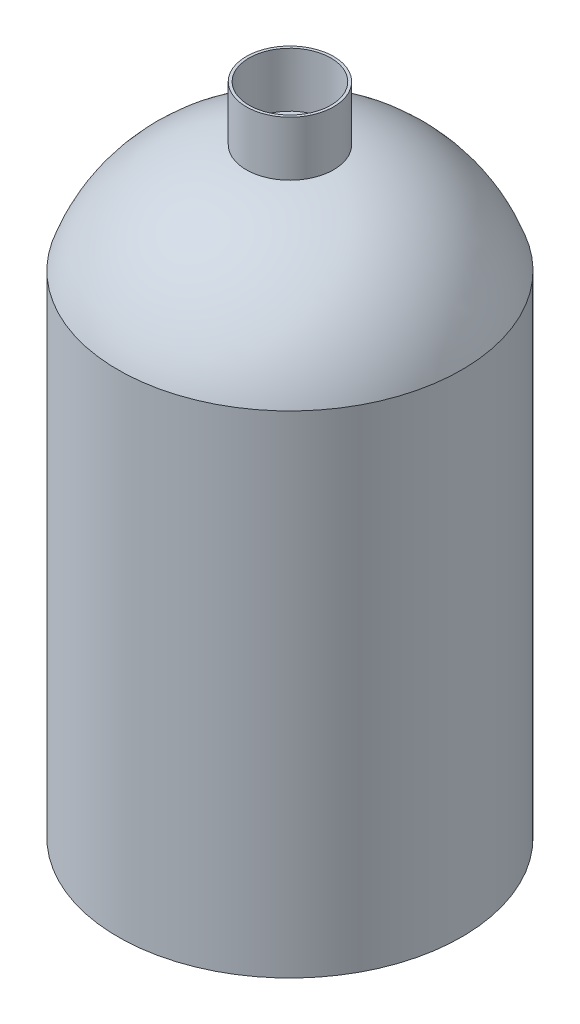
SolidWorks part; units mm, degrees
material "PVC 0.007 Plasticized"
ref_plane "Front Plane" through (0, 0, 0) normal (0, 0, 1) x (1, 0, 0)
ref_plane "Top Plane" through (0, 0, 0) normal (0, 1, 0) x (1, 0, 0)
ref_plane "Right Plane" through (0, 0, 0) normal (1, 0, 0) x (0, 0, -1)
sketch "Sketch2" plane through (0, 0, 0) normal (0, 0, 1) x (1, 0, 0)
  line L0 (0, 0) -> (0, 22)
  line L1 (0, 22) -> (-1.5, 22)
  line L2 (-1.5, 22) -> (-1.5, 24)
  line L3 (-1.5, 24) -> (-1.6, 24)
  line L4 (-1.6, 24) -> (-1.6, 22)
  line L5 (0, 0) -> (-6.3, 0)
  line L6 (-6.3, 0) -> (-6.3, 18)
  arc A1 (-1.6, 22) -> (-6.3, 18) centre (-0.615, 16.0814) ccw
  dimension "D7" = 6
  dimension "D1" = 22
  dimension "D2" = 6.3
  dimension "D3" = 1.5
  dimension "D4" = 0.1
  dimension "D5" = 2
  dimension "D6" = 2
  dimension "D8" = 4
revolve "Revolve2" add sketch "Sketch2" angle 360 about L0
